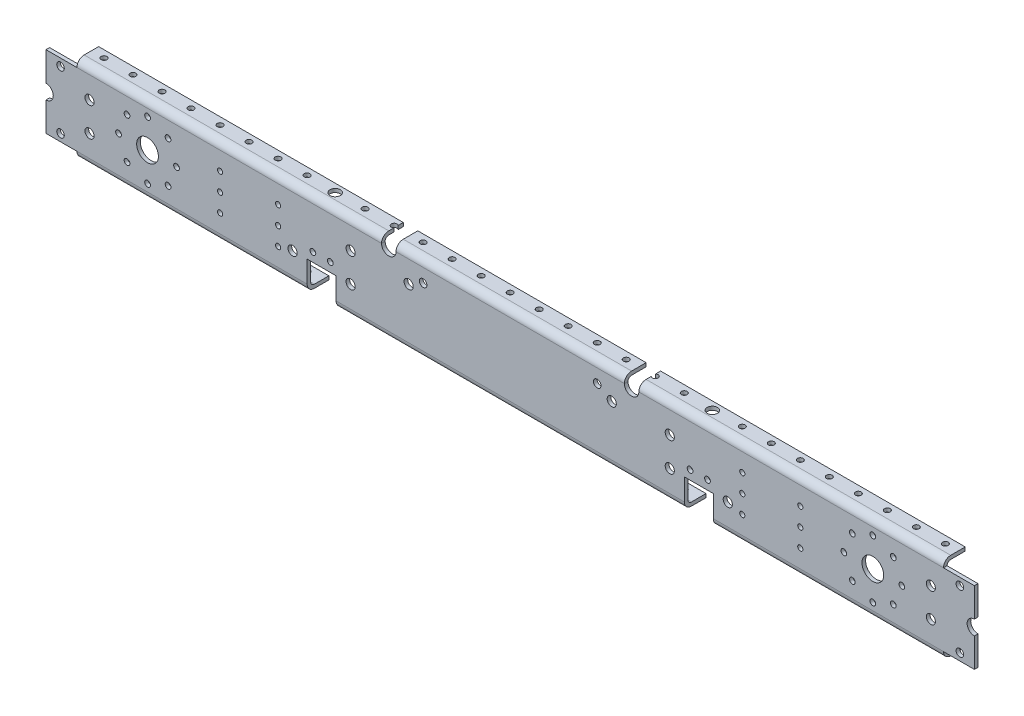
SolidWorks part; units mm, degrees
ref_plane "Front Plane" through (0, 0, 0) normal (0, 0, 1) x (1, 0, 0)
ref_plane "Top Plane" through (0, 0, 0) normal (0, 1, 0) x (1, 0, 0)
ref_plane "Right Plane" through (0, 0, 0) normal (1, 0, 0) x (0, 0, -1)
ref_plane "Plane1" through (0, 0, -3.175) normal (0, 0, -1) x (-1, 0, 0)
sketch "Sketch1" plane through (0, 0, -3.175) normal (0, 0, -1) x (-1, 0, 0)
  line L0 (-27.051, 0) -> (-785.749, 0)
  line L1 (-785.749, 0) -> (-785.749, -76.2)
  line L2 (-785.749, -76.2) -> (-27.051, -76.2)
  line L3 (-27.051, -76.2) -> (-27.051, 0)
extrude "Boss-Extrude1" add sketch "Sketch1" against normal blind 3.175
sketch "Sketch2" plane through (0, 0, -3.175) normal (0, 0, -1) x (-1, 0, 0)
  line L0 (-506.349, 0) -> (-519.049, 0)
  line L1 (-519.049, 0) -> (-519.049, -6.35)
  line L2 (-506.349, -6.35) -> (-506.349, 0)
  arc A0 (-519.049, -6.35) -> (-506.349, -6.35) centre (-512.699, -6.35) ccw
extrude "Cut-Extrude1" cut sketch "Sketch2" against normal through all
sketch "Sketch3" plane through (0, 0, -3.175) normal (0, 0, -1) x (-1, 0, 0)
  line L0 (-785.749, 0) -> (-519.049, 0)
  line L1 (-519.049, 0) -> (-519.049, -3.175)
  line L2 (-519.049, -3.175) -> (-785.749, -3.175)
  line L3 (-785.749, -3.175) -> (-785.749, 0)
extrude "Boss-Extrude2" add sketch "Sketch3" along normal blind 15.875
sketch "Sketch4" plane through (0, 0, -3.175) normal (0, 0, -1) x (-1, 0, 0)
  line L0 (-293.751, 0) -> (-306.451, 0)
  line L1 (-306.451, 0) -> (-306.451, -6.35)
  line L2 (-293.751, -6.35) -> (-293.751, 0)
  arc A0 (-306.451, -6.35) -> (-293.751, -6.35) centre (-300.101, -6.35) ccw
extrude "Cut-Extrude2" cut sketch "Sketch4" against normal through all
sketch "Sketch5" plane through (0, 0, -3.175) normal (0, 0, -1) x (-1, 0, 0)
  line L0 (-27.051, -3.175) -> (-293.751, -3.175)
  line L1 (-293.751, -3.175) -> (-293.751, 0)
  line L2 (-293.751, 0) -> (-27.051, 0)
  line L3 (-27.051, 0) -> (-27.051, -3.175)
extrude "Boss-Extrude3" add sketch "Sketch5" along normal blind 15.875
sketch "Sketch6" plane through (0, 0, -3.175) normal (0, 0, -1) x (-1, 0, 0)
  line L0 (-785.749, -76.2) -> (-228.6, -76.2)
  line L1 (-228.6, -76.2) -> (-228.6, -50.8)
  line L2 (-228.6, -50.8) -> (-785.749, -50.8)
  line L3 (-785.749, -50.8) -> (-785.749, -76.2)
extrude "Cut-Extrude3" cut sketch "Sketch6" against normal through all
sketch "Sketch7" plane through (0, 0, -3.175) normal (0, 0, -1) x (-1, 0, 0)
  line L0 (-27.051, -76.2) -> (-228.6, -76.2)
  line L1 (-228.6, -76.2) -> (-228.6, -73.025)
  line L2 (-228.6, -73.025) -> (-27.051, -73.025)
  line L3 (-27.051, -73.025) -> (-27.051, -76.2)
extrude "Boss-Extrude4" add sketch "Sketch7" along normal blind 15.875
sketch "Sketch8" plane through (0, -50.8, 0) normal (0, -1, 0) x (1, 0, 0)
  line L0 (785.749, -3.175) -> (584.2, -3.175)
  line L1 (584.2, -3.175) -> (584.2, 0)
  line L2 (584.2, 0) -> (785.749, 0)
  line L3 (785.749, 0) -> (785.749, -3.175)
extrude "Boss-Extrude5" add sketch "Sketch8" along normal blind 25.4
sketch "Sketch9" plane through (0, 0, -3.175) normal (0, 0, -1) x (-1, 0, 0)
  line L0 (-785.749, -73.025) -> (-584.2, -73.025)
  line L1 (-584.2, -73.025) -> (-584.2, -76.2)
  line L2 (-584.2, -76.2) -> (-785.749, -76.2)
  line L3 (-785.749, -76.2) -> (-785.749, -73.025)
extrude "Boss-Extrude6" add sketch "Sketch9" along normal blind 15.875
sketch "Sketch10" plane through (0, 0, -3.175) normal (0, 0, -1) x (-1, 0, 0)
  line L0 (-306.451, -3.175) -> (-506.349, -3.175)
  line L1 (-506.349, -3.175) -> (-506.349, 0)
  line L2 (-506.349, 0) -> (-306.451, 0)
  line L3 (-306.451, 0) -> (-306.451, -3.175)
extrude "Boss-Extrude7" add sketch "Sketch10" along normal blind 15.875
sketch "Sketch11" plane through (0, -50.8, 0) normal (0, -1, 0) x (1, 0, 0)
  line L0 (558.8, -3.175) -> (254, -3.175)
  line L1 (254, -3.175) -> (254, 0)
  line L2 (254, 0) -> (558.8, 0)
  line L3 (558.8, 0) -> (558.8, -3.175)
extrude "Boss-Extrude8" add sketch "Sketch11" along normal blind 25.4
sketch "Sketch12" plane through (0, 0, -3.175) normal (0, 0, -1) x (-1, 0, 0)
  line L0 (-254, -76.2) -> (-558.8, -76.2)
  line L1 (-558.8, -76.2) -> (-558.8, -73.025)
  line L2 (-558.8, -73.025) -> (-254, -73.025)
  line L3 (-254, -73.025) -> (-254, -76.2)
extrude "Boss-Extrude9" add sketch "Sketch12" along normal blind 15.875
sketch "Sketch13" plane through (785.749, 0, 0) normal (1, 0, 0) x (0, 0, -1)
  line L0 (3.175, -6.35) -> (3.175, -69.85)
  line L1 (3.175, -69.85) -> (0, -69.85)
  line L2 (0, -69.85) -> (0, -6.35)
  line L3 (0, -6.35) -> (3.175, -6.35)
extrude "Boss-Extrude10" add sketch "Sketch13" along normal blind 27.051
sketch "Sketch14" plane through (27.051, 0, 0) normal (-1, 0, 0) x (0, 0, 1)
  line L0 (-3.175, -69.85) -> (-3.175, -6.35)
  line L1 (-3.175, -6.35) -> (0, -6.35)
  line L2 (0, -6.35) -> (0, -69.85)
  line L3 (0, -69.85) -> (-3.175, -69.85)
extrude "Boss-Extrude11" add sketch "Sketch14" along normal blind 27.051
hole_wizard "M18 Clearance Hole1" positions "Sketch16" profile "Sketch15" hole size "M18" standard "ANSI Metric"
sketch "Sketch16" plane through (0, 0, 0) normal (0, 0, 1) x (1, 0, 0)
  point P0 (723.9, -38.1)
  point P1 (88.9, -38.1)
sketch "Sketch15" plane through (723.9, -38.1, 0) normal (1, 0, 0) x (0, -1, 0)
  line L0 (0, 0) -> (0, 19.05)
  line L1 (0, 19.05) -> (9.525, 19.05)
  line L2 (9.525, 19.05) -> (9.525, 0)
  line L5 (9.525, 0) -> (0, 0)
  line L11 (0, -6.35) -> (0, 107.95) construction
  dimension "Thru Hole Dia." = 19.05
  dimension "Thru Hole Depth" = 19.05
hole_wizard "Ø5.0 (5) Diameter Hole1" positions "Sketch18" profile "Sketch17" hole size "Ø5.0" standard "ANSI Metric"
sketch "Sketch18" plane through (0, 0, 0) normal (0, 0, 1) x (1, 0, 0)
  circle A0 centre (723.9, -38.1) radius 9.525 construction
  circle A1 centre (88.9, -38.1) radius 9.525 construction
  point P0 (233.68, -42.8625)
  point P1 (248.92, -42.8625)
  point P2 (698.5, -38.1)
  point P3 (749.3, -38.1)
  point P4 (741.8605, -56.0605)
  point P5 (705.9395, -20.1395)
  point P6 (705.9395, -56.0605)
  point P7 (741.8605, -20.1395)
  point P8 (723.9, -63.5)
  point P9 (723.9, -12.7)
  point P10 (114.3, -38.1)
  point P11 (63.5, -38.1)
  point P12 (70.9395, -56.0605)
  point P13 (106.8605, -20.1395)
  point P14 (106.8605, -56.0605)
  point P15 (70.9395, -20.1395)
  point P16 (88.9, -63.5)
  point P17 (88.9, -12.7)
  point P18 (563.88, -42.8625)
  point P19 (579.12, -42.8625)
  point P22 (0, 0)
  dimension "D9" = 25.4
  dimension "D12" = 25.4
  dimension "D13" = 25.4
  dimension "D14" = 25.4
  dimension "D15" = 25.4
  dimension "D1" = 25.4
  dimension "D2" = 25.4
  dimension "D3" = 25.4
  dimension "D4" = 25.4
  dimension "D5" = 25.4
  dimension "D6" = 25.4
  dimension "D7" = 25.4
  dimension "D8" = 25.4
  dimension "D10" = 25.4
  dimension "D11" = 25.4
  dimension "D16" = 25.4
sketch "Sketch17" plane through (233.68, -42.8625, 0) normal (1, 0, 0) x (0, -1, 0)
  line L0 (0, 0) -> (0, 19.05)
  line L1 (0, 19.05) -> (2.5, 19.05)
  line L2 (2.5, 19.05) -> (2.5, 0)
  line L5 (2.5, 0) -> (0, 0)
  line L11 (0, -6.35) -> (0, 107.95) construction
  dimension "Thru Hole Dia." = 5
  dimension "Thru Hole Depth" = 19.05
hole_wizard "M4 Clearance Hole1" positions "Sketch20" profile "Sketch19" hole size "M4" standard "ANSI Metric"
sketch "Sketch20" plane through (0, 0, 0) normal (0, 0, 1) x (1, 0, 0)
  point P0 (152.4, -38.1)
  point P1 (203.2, -38.1)
  point P2 (152.4, -22.225)
  point P3 (152.4, -53.975)
  point P4 (203.2, -53.975)
  point P5 (203.2, -22.225)
  point P6 (609.6, -22.225)
  point P7 (609.6, -53.975)
  point P8 (660.4, -53.975)
  point P9 (660.4, -22.225)
  point P10 (609.6, -38.1)
  point P11 (660.4, -38.1)
sketch "Sketch19" plane through (152.4, -38.1, 0) normal (1, 0, 0) x (0, -1, 0)
  line L0 (0, 0) -> (0, 19.05)
  line L1 (0, 19.05) -> (2.2479, 19.05)
  line L2 (2.2479, 19.05) -> (2.2479, 0)
  line L5 (2.2479, 0) -> (0, 0)
  line L11 (0, -6.35) -> (0, 107.95) construction
  dimension "Thru Hole Dia." = 4.4958
  dimension "Thru Hole Depth" = 19.05
hole_wizard "Ø6.6 (6.6) Diameter Hole1" positions "Sketch22" profile "Sketch21" hole size "Ø6.6" standard "ANSI Metric"
sketch "Sketch22" plane through (0, 0, 0) normal (0, 0, 1) x (1, 0, 0)
  point P0 (800.1, -63.5)
  point P1 (482.6, -18.2183)
  point P2 (800.1, -12.7)
  point P3 (12.7, -63.5)
  point P4 (330.2, -18.2183)
  point P5 (12.7, -12.7)
sketch "Sketch21" plane through (800.1, -63.5, 0) normal (1, 0, 0) x (0, -1, 0)
  line L0 (0, 0) -> (0, 19.05)
  line L1 (0, 19.05) -> (3.3, 19.05)
  line L2 (3.3, 19.05) -> (3.3, 0)
  line L5 (3.3, 0) -> (0, 0)
  line L11 (0, -6.35) -> (0, 107.95) construction
  dimension "Thru Hole Dia." = 6.6
  dimension "Thru Hole Depth" = 19.05
hole_wizard "Ø8.0 (8) Diameter Hole1" positions "Sketch24" profile "Sketch23" hole size "Ø8.0" standard "ANSI Metric"
sketch "Sketch24" plane through (0, 0, 0) normal (0, 0, 1) x (1, 0, 0)
  point P0 (596.9, -50.8)
  point P1 (317.5, -25.4)
  point P2 (38.1, -25.4)
  point P3 (215.9, -50.8)
  point P4 (495.3, -25.4)
  point P5 (774.7, -50.8)
  point P6 (546.1, -50.8)
  point P7 (266.7, -25.4)
  point P8 (38.1, -50.8)
  point P9 (266.7, -50.8)
  point P10 (546.1, -25.4)
  point P11 (774.7, -25.4)
sketch "Sketch23" plane through (596.9, -50.8, 0) normal (1, 0, 0) x (0, -1, 0)
  line L0 (0, 0) -> (0, 19.05)
  line L1 (0, 19.05) -> (4, 19.05)
  line L2 (4, 19.05) -> (4, 0)
  line L5 (4, 0) -> (0, 0)
  line L11 (0, -6.35) -> (0, 107.95) construction
  dimension "Thru Hole Dia." = 8
  dimension "Thru Hole Depth" = 19.05
hole_wizard "Hole1" positions "Sketch26" profile "Sketch25" legacy
sketch "Sketch26" plane through (0, 0, -3.175) normal (0, 0, -1) x (-1, 0, 0)
  point P0 (-812.8, -38.1)
  point P1 (0, -38.1)
sketch "Sketch25" plane through (812.8, -38.1, -3.175) normal (1, 0, 0) x (0, 1, 0)
  line L0 (0, 0) -> (0, 3.175)
  line L1 (0, 3.175) -> (6.35, 3.175)
  line L2 (6.35, 3.175) -> (6.35, 0)
  line L3 (6.35, 0) -> (0, 0)
  line L4 (0, 110) -> (0, -10) construction
  dimension "Diameter" = 12.7
  dimension "Depth" = 3.175
hole_wizard "Ø5.0 (5) Diameter Hole2" positions "Sketch28" profile "Sketch27" hole size "Ø5.0" standard "ANSI Metric"
sketch "Sketch28" plane through (0, -76.2, 0) normal (0, -1, 0) x (-1, 0, 0)
  point P0 (-165.1, 12.7)
  point P1 (-63.5, 12.7)
  point P2 (-88.9, 12.7)
  point P3 (-190.5, 12.7)
  point P4 (-139.7, 12.7)
  point P5 (-38.1, 12.7)
  point P6 (-114.3, 12.7)
  point P7 (-215.9, 12.7)
  point P8 (-495.3, 12.7)
  point P9 (-393.7, 12.7)
  point P10 (-292.1, 12.7)
  point P11 (-317.5, 12.7)
  point P12 (-419.1, 12.7)
  point P13 (-520.7, 12.7)
  point P14 (-469.9, 12.7)
  point P15 (-368.3, 12.7)
  point P16 (-266.7, 12.7)
  point P17 (-342.9, 12.7)
  point P18 (-444.5, 12.7)
  point P19 (-546.1, 12.7)
  point P20 (-723.9, 12.7)
  point P21 (-622.3, 12.7)
  point P22 (-647.7, 12.7)
  point P23 (-749.3, 12.7)
  point P24 (-698.5, 12.7)
  point P25 (-596.9, 12.7)
  point P26 (-673.1, 12.7)
  point P27 (-774.7, 12.7)
sketch "Sketch27" plane through (165.1, -76.2, -12.7) normal (1, 0, 0) x (0, 0, -1)
  line L0 (0, 0) -> (0, 3.175)
  line L1 (0, 3.175) -> (2.5, 3.175)
  line L2 (2.5, 3.175) -> (2.5, 0)
  line L5 (2.5, 0) -> (0, 0)
  line L11 (0, -6.35) -> (0, 107.95) construction
  dimension "Thru Hole Dia." = 5
  dimension "Thru Hole Depth" = 3.175
hole_wizard "Ø5.0 (5) Diameter Hole3" positions "Sketch30" profile "Sketch29" hole size "Ø5.0" standard "ANSI Metric"
sketch "Sketch30" plane through (0, -3.175, 0) normal (0, -1, 0) x (-1, 0, 0)
  point P0 (-774.7, 12.7)
  point P1 (-673.1, 12.7)
  point P2 (-546.1, 12.7)
  point P3 (-596.9, 12.7)
  point P4 (-698.5, 12.7)
  point P5 (-749.3, 12.7)
  point P6 (-647.7, 12.7)
  point P7 (-622.3, 12.7)
  point P8 (-723.9, 12.7)
  point P9 (-495.3, 12.7)
  point P10 (-393.7, 12.7)
  point P11 (-317.5, 12.7)
  point P12 (-419.1, 12.7)
  point P13 (-469.9, 12.7)
  point P14 (-368.3, 12.7)
  point P15 (-342.9, 12.7)
  point P16 (-444.5, 12.7)
  point P17 (-292.1, 12.7)
  point P18 (-215.9, 12.7)
  point P19 (-114.3, 12.7)
  point P20 (-38.1, 12.7)
  point P21 (-139.7, 12.7)
  point P22 (-266.7, 12.7)
  point P23 (-190.5, 12.7)
  point P24 (-88.9, 12.7)
  point P25 (-63.5, 12.7)
  point P26 (-165.1, 12.7)
sketch "Sketch29" plane through (774.7, -3.175, -12.7) normal (1, 0, 0) x (0, 0, -1)
  line L0 (0, 0) -> (0, 3.175)
  line L1 (0, 3.175) -> (2.5, 3.175)
  line L2 (2.5, 3.175) -> (2.5, 0)
  line L5 (2.5, 0) -> (0, 0)
  line L11 (0, -6.35) -> (0, 107.95) construction
  dimension "Thru Hole Dia." = 5
  dimension "Thru Hole Depth" = 3.175
hole_wizard "Ø9.0 (9) Diameter Hole1" positions "Sketch32" profile "Sketch31" hole size "Ø9.0" standard "ANSI Metric"
sketch "Sketch32" plane through (0, 0, 0) normal (0, 1, 0) x (1, 0, 0)
  point P0 (571.5, 11.8683)
  point P1 (241.3, 11.8683)
sketch "Sketch31" plane through (571.5, 0, -11.8683) normal (1, 0, 0) x (0, 0, 1)
  line L0 (0, 0) -> (0, 76.2)
  line L1 (0, 76.2) -> (4.5, 76.2)
  line L2 (4.5, 76.2) -> (4.5, 0)
  line L5 (4.5, 0) -> (0, 0)
  line L11 (0, -6.35) -> (0, 107.95) construction
  dimension "Thru Hole Dia." = 9
  dimension "Thru Hole Depth" = 76.2
hole_wizard "Ø5.0 (5) Diameter Hole4" positions "Sketch34" profile "Sketch33" hole size "Ø5.0" standard "ANSI Metric"
sketch "Sketch34" plane through (0, 0, 0) normal (0, 1, 0) x (1, 0, 0)
  point P0 (520.7, 12.7)
sketch "Sketch33" plane through (520.7, 0, -12.7) normal (1, 0, 0) x (0, 0, 1)
  line L0 (0, 0) -> (0, 76.2)
  line L1 (0, 76.2) -> (2.5, 76.2)
  line L2 (2.5, 76.2) -> (2.5, 0)
  line L5 (2.5, 0) -> (0, 0)
  line L11 (0, -6.35) -> (0, 107.95) construction
  dimension "Thru Hole Dia." = 5
  dimension "Thru Hole Depth" = 76.2
fillet "Fillet1" radius 3.175 6 edges at (127.8255, -73.025, -3.175) (160.401, -3.175, -3.175) (406.4, -3.175, -3.175) (406.4, -73.025, -3.175) (652.399, -3.175, -3.175) (684.9745, -73.025, -3.175)
fillet "Fillet2" radius 6.35 6 edges at (652.399, 0, 0) (160.401, 0, 0) (406.4, 0, 0) (127.8255, -76.2, 0) (684.9745, -76.2, 0) (406.4, -76.2, 0)
